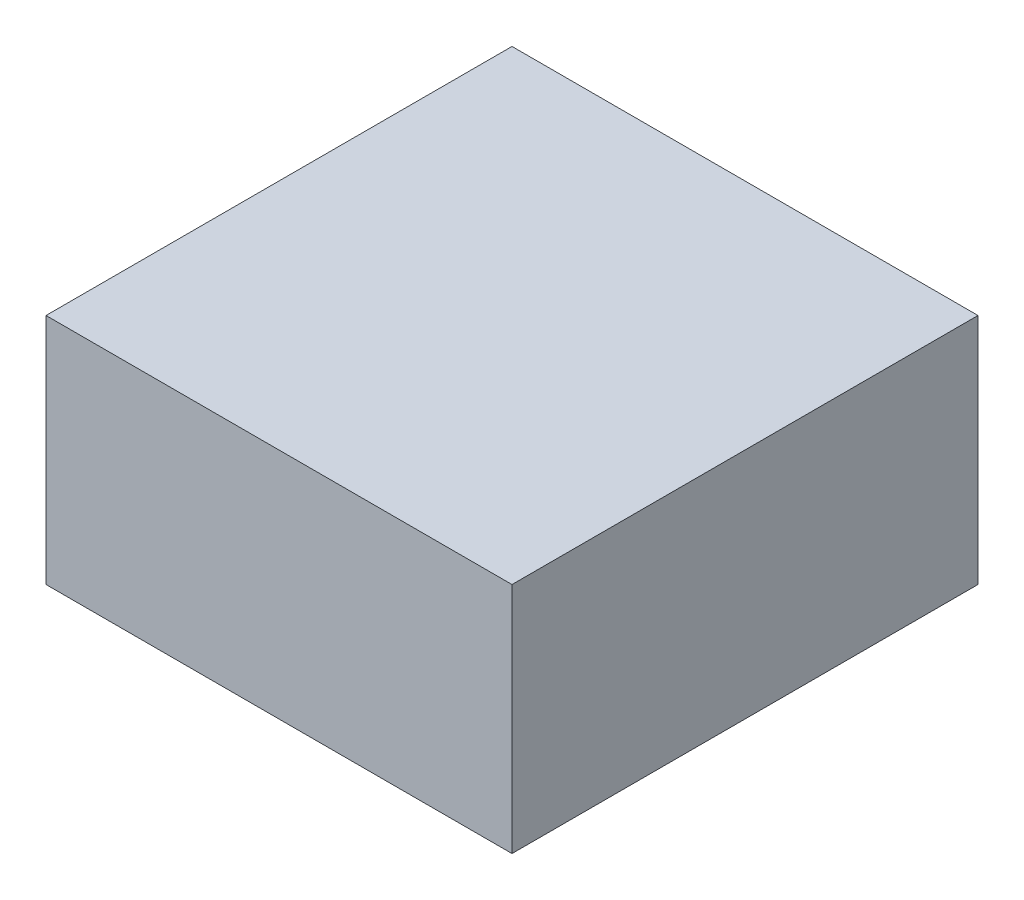
SolidWorks part; units mm, degrees
ref_plane "Front Plane" through (0, 0, 0) normal (0, 0, 1) x (1, 0, 0)
ref_plane "Top Plane" through (0, 0, 0) normal (0, 1, 0) x (1, 0, 0)
ref_plane "Right Plane" through (0, 0, 0) normal (1, 0, 0) x (0, 0, -1)
sketch "Sketch1" plane through (0, 0, 0) normal (0, 1, 0) x (1, 0, 0)
  line L1 (5.4341, 80.9119) -> (45.4341, 80.9119)
  line L2 (5.4341, 80.9119) -> (5.4341, 40.9119)
  line L3 (5.4341, 40.9119) -> (45.4341, 40.9119)
  line L4 (45.4341, 80.9119) -> (45.4341, 40.9119)
  line L5 (5.4341, 80.9119) -> (45.4341, 40.9119) construction
  line L6 (5.4341, 40.9119) -> (45.4341, 80.9119) construction
  point P0 (25.4341, 60.9119)
extrude "Boss-Extrude1" add sketch "Sketch1" along normal blind 20
